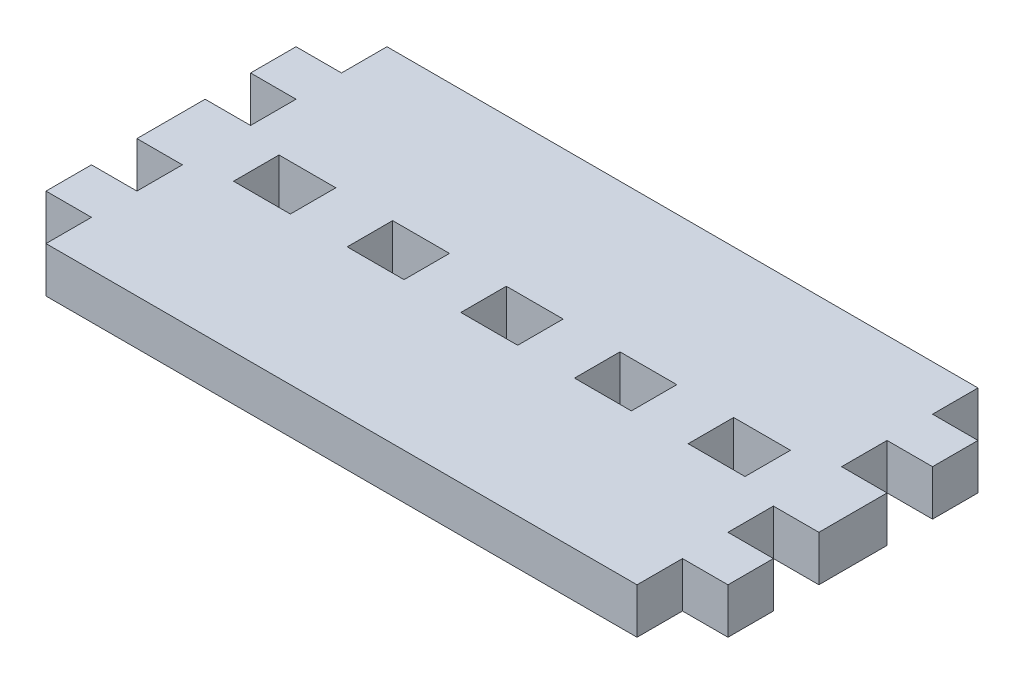
SolidWorks part; units mm, degrees
ref_plane "Front Plane" through (0, 0, 0) normal (0, 0, 1) x (1, 0, 0)
ref_plane "Top Plane" through (0, 0, 0) normal (0, 1, 0) x (1, 0, 0)
ref_plane "Right Plane" through (0, 0, 0) normal (1, 0, 0) x (0, 0, -1)
sketch "Sketch1" plane through (0, 0, 0) normal (0, 1, 0) x (1, 0, 0)
  line L1 (-25.527, 20.2565) -> (50.673, 20.2565)
  line L2 (-25.527, 20.2565) -> (-25.527, -17.8435)
  line L3 (-25.527, -17.8435) -> (50.673, -17.8435)
  line L4 (50.673, 20.2565) -> (50.673, -17.8435)
  dimension "D1" = 76.2
  dimension "D2" = 38.1
extrude "Boss-Extrude1" add sketch "Sketch1" along normal blind 5.08
sketch "Sketch2" plane through (0, 5.08, 0) normal (0, 1, 0) x (1, 0, 0)
  line L0 (12.573, 20.2565) -> (12.573, -17.8435) construction
  line L1 (50.673, 20.2565) -> (-25.527, 20.2565) construction
  line L2 (-25.527, -17.8435) -> (50.673, -17.8435) construction
  line L3 (45.593, 20.2565) -> (45.593, -18.4159) construction
  line L4 (50.673, -17.8435) -> (50.673, 20.2565) construction
  line L5 (-20.447, -7.6835) -> (-20.447, -2.6035)
  line L6 (50.673, 20.2565) -> (45.593, 20.2565)
  line L7 (50.673, 20.2565) -> (50.673, 15.1765)
  line L8 (50.673, 15.1765) -> (45.593, 15.1765)
  line L9 (45.593, 20.2565) -> (45.593, 15.1765)
  line L10 (50.673, 10.0965) -> (45.593, 10.0965)
  line L11 (50.673, 10.0965) -> (50.673, 5.0165)
  line L12 (50.673, 5.0165) -> (45.593, 5.0165)
  line L13 (45.593, 10.0965) -> (45.593, 5.0165)
  line L14 (50.673, -17.8435) -> (45.593, -17.8435)
  line L15 (50.673, -17.8435) -> (50.673, -12.7635)
  line L16 (50.673, -12.7635) -> (45.593, -12.7635)
  line L17 (45.593, -17.8435) -> (45.593, -12.7635)
  line L18 (50.673, -7.6835) -> (45.593, -7.6835)
  line L19 (50.673, -7.6835) -> (50.673, -2.6035)
  line L20 (50.673, -2.6035) -> (45.593, -2.6035)
  line L21 (45.593, -7.6835) -> (45.593, -2.6035)
  line L22 (-25.527, -2.6035) -> (-20.447, -2.6035)
  line L23 (-25.527, -7.6835) -> (-25.527, -2.6035)
  line L24 (-25.527, -7.6835) -> (-20.447, -7.6835)
  line L25 (-20.447, -17.8435) -> (-20.447, -12.7635)
  line L26 (-25.527, -12.7635) -> (-20.447, -12.7635)
  line L27 (-25.527, -17.8435) -> (-25.527, -12.7635)
  line L28 (-25.527, -17.8435) -> (-20.447, -17.8435)
  line L29 (-20.447, 10.0965) -> (-20.447, 5.0165)
  line L30 (-25.527, 5.0165) -> (-20.447, 5.0165)
  line L31 (-25.527, 10.0965) -> (-25.527, 5.0165)
  line L32 (-25.527, 10.0965) -> (-20.447, 10.0965)
  line L33 (-20.447, 20.2565) -> (-20.447, 15.1765)
  line L34 (-25.527, 15.1765) -> (-20.447, 15.1765)
  line L35 (-25.527, 20.2565) -> (-25.527, 15.1765)
  line L36 (-25.527, 20.2565) -> (-20.447, 20.2565)
  dimension "D1" = 5.08
  dimension "D2" = 7.62
  dimension "D3" = 5.08
  dimension "D4" = 5.08
  dimension "D5" = 5.08
  dimension "D6" = 5.08
  dimension "D7" = 5.08
extrude "Cut-Extrude1" cut sketch "Sketch2" against normal blind 5.08
sketch "Sketch3" plane through (0, 5.08, 0) normal (0, 1, 0) x (1, 0, 0)
  line L0 (12.573, 20.2565) -> (12.573, -17.8435) construction
  line L1 (45.593, 20.2565) -> (-20.447, 20.2565) construction
  line L2 (-20.447, -17.8435) -> (45.593, -17.8435) construction
  line L3 (-25.527, 1.2065) -> (50.673, 1.2065) construction
  line L4 (-25.527, 5.0165) -> (-25.527, -2.6035) construction
  line L5 (50.673, -2.6035) -> (50.673, 5.0165) construction
  line L34 (-27.9561, 3.7465) -> (55.2474, 3.7465) construction
  line L35 (-36.4943, -1.3335) -> (65.0942, -1.3335) construction
  line L36 (-16.002, 3.7465) -> (-16.002, -1.3335)
  line L37 (9.398, 3.7465) -> (15.748, 3.7465)
  line L38 (9.398, 3.7465) -> (9.398, -1.3335)
  line L39 (9.398, -1.3335) -> (15.748, -1.3335)
  line L40 (15.748, 3.7465) -> (15.748, -1.3335)
  line L41 (22.098, 3.7465) -> (28.448, 3.7465)
  line L42 (22.098, 3.7465) -> (22.098, -1.3335)
  line L43 (22.098, -1.3335) -> (28.448, -1.3335)
  line L44 (28.448, 3.7465) -> (28.448, -1.3335)
  line L45 (34.798, 3.7465) -> (41.148, 3.7465)
  line L46 (34.798, 3.7465) -> (34.798, -1.3335)
  line L47 (34.798, -1.3335) -> (41.148, -1.3335)
  line L48 (41.148, 3.7465) -> (41.148, -1.3335)
  line L49 (-9.652, -1.3335) -> (-16.002, -1.3335)
  line L50 (-9.652, 3.7465) -> (-9.652, -1.3335)
  line L51 (-9.652, 3.7465) -> (-16.002, 3.7465)
  line L52 (-3.302, 3.7465) -> (-3.302, -1.3335)
  line L53 (3.048, -1.3335) -> (-3.302, -1.3335)
  line L54 (3.048, 3.7465) -> (3.048, -1.3335)
  line L55 (3.048, 3.7465) -> (-3.302, 3.7465)
  dimension "D1" = 2.54
  dimension "D2" = 2.54
  dimension "D3" = 6.35
  dimension "D4" = 3.175
  dimension "D5" = 6.35
  dimension "D6" = 6.35
  dimension "D7" = 6.35
  dimension "D8" = 6.35
extrude "Cut-Extrude2" cut sketch "Sketch3" against normal blind 5.08
